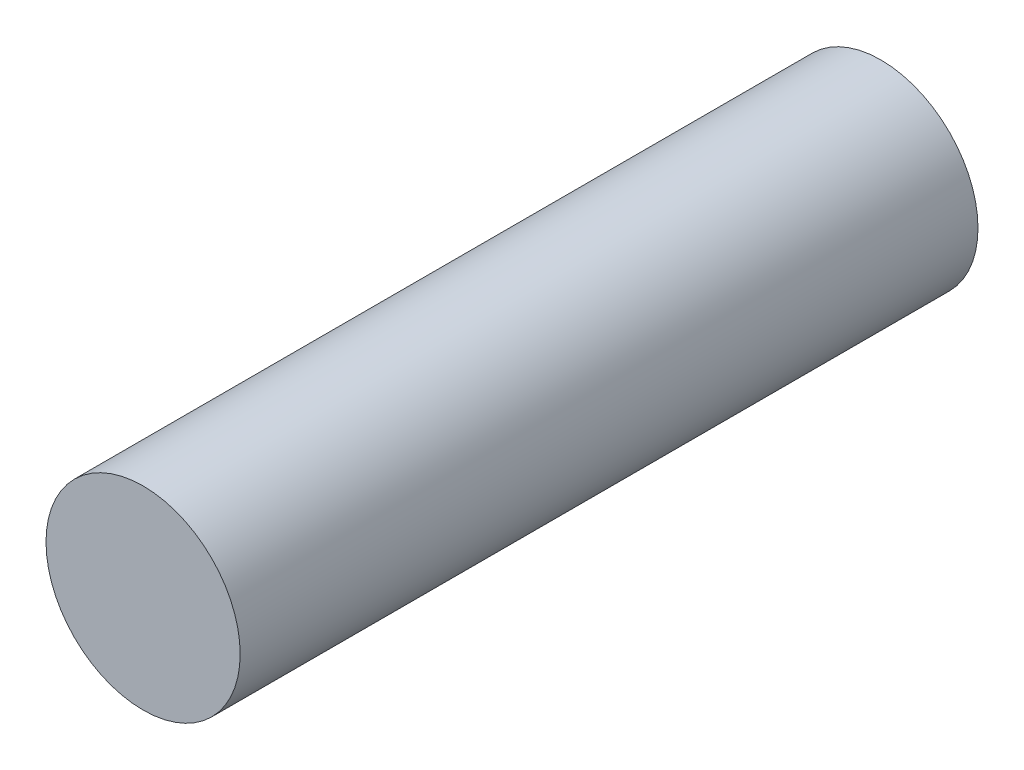
SolidWorks part; units mm, degrees
ref_plane "Front Plane" through (0, 0, 0) normal (0, 0, 1) x (1, 0, 0)
ref_plane "Top Plane" through (0, 0, 0) normal (0, 1, 0) x (1, 0, 0)
ref_plane "Right Plane" through (0, 0, 0) normal (1, 0, 0) x (0, 0, -1)
sketch "Sketch1" plane through (0, 0, 0) normal (0, 0, 1) x (1, 0, 0)
  circle A0 centre (0, 0) radius 2.5
  dimension "D1" = 5
extrude "Boss-Extrude1" add sketch "Sketch1" along normal blind 19
ref_point "Centre"
